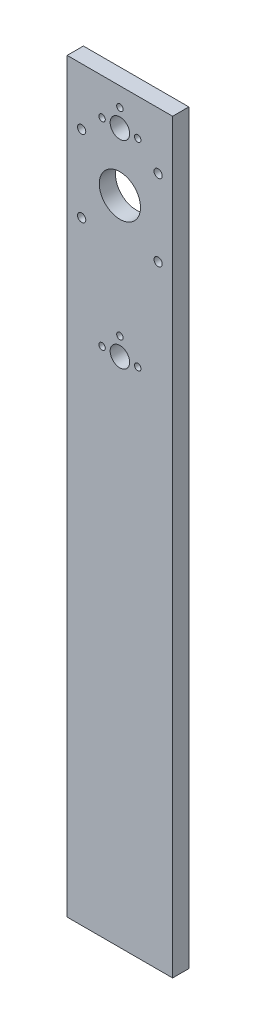
SolidWorks part; units mm, degrees
ref_plane "Front Plane" through (0, 0, 0) normal (0, 0, 1) x (1, 0, 0)
ref_plane "Top Plane" through (0, 0, 0) normal (0, 1, 0) x (1, 0, 0)
ref_plane "Right Plane" through (0, 0, 0) normal (1, 0, 0) x (0, 0, -1)
sketch "Sketch1" plane through (0, 0, 0) normal (0, 0, 1) x (1, 0, 0)
  line L0 (-18, -106) -> (18, -106) construction
  line L1 (0, 28.575) -> (0, -371.425) construction
  line L2 (-32.5, 38.575) -> (32.5, 38.575)
  line L3 (-42.5, 38.575) -> (42.5, 38.575) construction
  line L4 (-32.5, -371.425) -> (-32.5, 28.575) construction
  line L5 (32.5, -371.425) -> (32.5, 28.575) construction
  line L6 (-18, 16) -> (18, 16) construction
  line L8 (23.5712, -43.5712) -> (-23.5712, -43.5712) construction
  line L9 (23.5712, -43.5712) -> (23.5712, 3.5712) construction
  line L10 (23.5712, 3.5712) -> (-23.5712, 3.5712) construction
  line L11 (-23.5712, -43.5712) -> (-23.5712, 3.5712) construction
  line L12 (23.5712, -43.5712) -> (-23.5712, 3.5712) construction
  line L13 (23.5712, 3.5712) -> (-23.5712, -43.5712) construction
  line L14 (-32.5, -421.425) -> (32.5, -421.425)
  line L15 (-82.5, -421.425) -> (82.5, -421.425) construction
  line L16 (-32.5, -421.425) -> (-32.5, 38.575)
  line L17 (-32.5, -371.425) -> (-32.5, 38.575) construction
  line L18 (32.5, -421.425) -> (32.5, 38.575)
  line L20 (32.5, -371.425) -> (32.5, 38.575) construction
  line L21 (-42.5, -381.425) -> (-42.5, 38.575) construction
  line L22 (42.5, -381.425) -> (42.5, 38.575) construction
  line L23 (-32.5, 28.575) -> (32.5, 28.575) construction
  line L24 (-42.5, -381.425) -> (42.5, -381.425) construction
  line L25 (82.5, -421.425) -> (82.5, 88.575) construction
  line L26 (-32.5, -371.425) -> (32.5, -371.425) construction
  line L27 (-82.5, -421.425) -> (-82.5, 88.575) construction
  line L28 (-82.5, 88.575) -> (82.5, 88.575) construction
  circle A0 centre (-23.5712, 3.5712) radius 2.54
  circle A1 centre (23.5712, 3.5712) radius 2.54
  circle A2 centre (23.5712, -43.5712) radius 2.54
  circle A3 centre (-23.5712, -43.5712) radius 2.54
  circle A4 centre (0, -20) radius 28.575 construction
  circle A5 centre (0, -106) radius 6
  circle A6 centre (0, -106) radius 11 construction
  circle A7 centre (11, -106) radius 2
  circle A8 centre (0, -20) radius 12.7
  circle A10 centre (0, -95) radius 2
  circle A12 centre (0, 16) radius 6
  circle A13 centre (11, 16) radius 2
  circle A14 centre (-11, -106) radius 2
  circle A15 centre (0, 27) radius 2
  circle A16 centre (-11, 16) radius 2
  circle A17 centre (0, 16) radius 11 construction
  point P0 (0, -20)
  point P8 (0, -20)
  point P37 (0, -171.425)
  dimension "D5" = 5.08
  dimension "D8" = 36
  dimension "D9" = 2
  dimension "D2" = 25.4
  dimension "D6" = 57.15
  dimension "D1" = 65
  dimension "D3" = 47.1424
  dimension "D4" = 47.1424
  dimension "D10" = 122
extrude "Boss-Extrude1" add sketch "Sketch1" along normal blind 10
